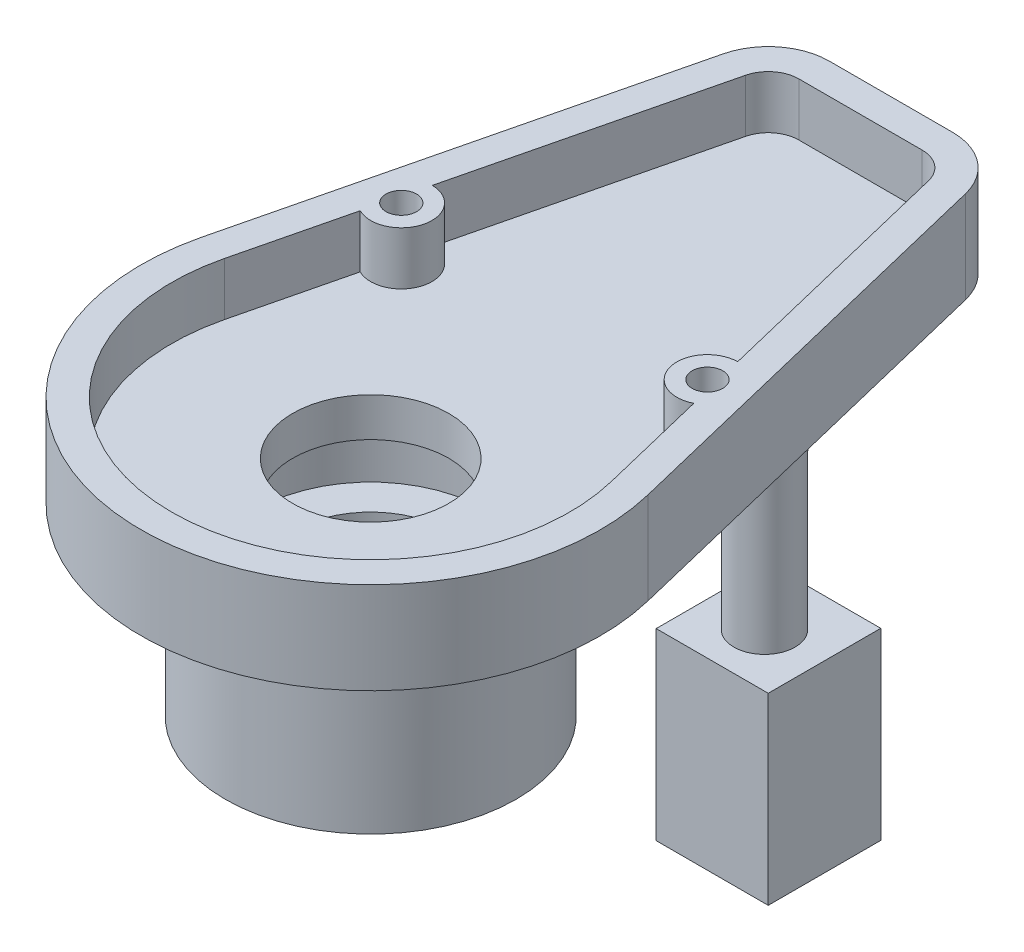
SolidWorks part; units mm, degrees
other "Markup2"
sketch "Sketch12"
other "Markup3"
sketch "Sketch13"
ref_plane "Front Plane" through (0, 0, 0) normal (0, 0, 1) x (1, 0, 0)
ref_plane "Top Plane" through (0, 0, 0) normal (0, 1, 0) x (1, 0, 0)
ref_plane "Right Plane" through (0, 0, 0) normal (1, 0, 0) x (0, 0, -1)
sketch "Sketch1" plane through (0, 0, 0) normal (0, 1, 0) x (1, 0, 0)
  line L0 (0, 0) -> (0, 0.16) construction
  line L1 (0.0201, 0.16) -> (-0.0201, 0.16)
  line L2 (-0.0299, 0.1524) -> (-0.0499, 0.07)
  line L3 (0.0299, 0.1524) -> (0.0499, 0.07)
  line L4 (-0.0396, 0.1547) -> (-0.0729, 0.0177)
  line L5 (0.0396, 0.1547) -> (0.0729, 0.0177)
  line L6 (0.0201, 0.17) -> (-0.0201, 0.17)
  line L7 (0, 0) -> (0, 0.06) construction
  line L8 (0.05, 0.06) -> (-0.05, 0.06) construction
  line L9 (-0.0545, 0.0511) -> (-0.0632, 0.0154)
  line L10 (0.0545, 0.0511) -> (0.0632, 0.0154)
  line L11 (-0.0299, 0.1524) -> (-0.0632, 0.0154) construction
  line L13 (0.0299, 0.1524) -> (0.0632, 0.0154) construction
  arc A1 (-0.0632, 0.0154) -> (0.0632, 0.0154) centre (0, 0) ccw
  arc A2 (0.0201, 0.16) -> (0.0299, 0.1524) centre (0.0201, 0.15) cw
  arc A3 (-0.0201, 0.16) -> (-0.0299, 0.1524) centre (-0.0201, 0.15) ccw
  arc A4 (-0.0729, 0.0177) -> (0.0729, 0.0177) centre (0, 0) ccw
  arc A5 (0.0201, 0.17) -> (0.0396, 0.1547) centre (0.0201, 0.15) cw
  arc A6 (-0.0201, 0.17) -> (-0.0396, 0.1547) centre (-0.0201, 0.15) ccw
  circle A7 centre (-0.05, 0.06) radius 0.005
  circle A8 centre (0.05, 0.06) radius 0.005
  arc A10 (-0.0545, 0.0511) -> (-0.0499, 0.07) centre (-0.05, 0.06) ccw
  arc A11 (0.0499, 0.07) -> (0.0545, 0.0511) centre (0.05, 0.06) ccw
  circle A12 centre (0.05, 0.06) radius 0.01 construction
  circle A13 centre (-0.05, 0.06) radius 0.01 construction
  point P8 (0, 0.16)
  point P13 (0, 0.06)
  point P17 (0.028, 0.16)
  point P20 (-0.028, 0.16)
  point P31 (0.06, 0.06)
  point P37 (-0.04, 0.06)
  dimension "D1" = 0.01
  dimension "D2" = 0.13
  dimension "D3" = 0.16
  dimension "D5" = 0.01
  dimension "D6" = 0.06
  dimension "D8" = 0.01
  dimension "D9" = 0.01
  dimension "D10" = 0.005
  dimension "D4" = 0.056
  dimension "D7" = 0.1
extrude "Boss-Extrude1" add sketch "Sketch1" along normal blind 0.03
sketch "Sketch6" plane through (0, 0, 0) normal (0, -1, 0) x (1, 0, 0)
  line L3 (-0.0201, -0.17) -> (0.0201, -0.17)
  line L4 (0.0396, -0.1547) -> (0.0729, -0.0177)
  line L5 (-0.0729, -0.0177) -> (-0.0396, -0.1547)
  line L6 (-0.0201, -0.17) -> (0.0201, -0.17)
  line L7 (0.0396, -0.1547) -> (0.0729, -0.0177)
  line L8 (-0.0729, -0.0177) -> (-0.0396, -0.1547)
  circle A0 centre (0, 0) radius 0.0255
  arc A1 (0.0632, -0.0154) -> (-0.0632, -0.0154) centre (0, 0) ccw construction
  arc A3 (-0.0396, -0.1547) -> (-0.0201, -0.17) centre (-0.0201, -0.15) ccw
  arc A4 (0.0201, -0.17) -> (0.0396, -0.1547) centre (0.0201, -0.15) ccw
  arc A5 (0.0729, -0.0177) -> (-0.0729, -0.0177) centre (0, 0) ccw
  arc A6 (-0.0396, -0.1547) -> (-0.0201, -0.17) centre (-0.0201, -0.15) ccw
  arc A7 (0.0201, -0.17) -> (0.0396, -0.1547) centre (0.0201, -0.15) ccw
  arc A8 (0.0729, -0.0177) -> (-0.0729, -0.0177) centre (0, 0) ccw
  dimension "D2" = 0.051
  dimension "D1" = 0
extrude "Boss-Extrude5" add sketch "Sketch6" against normal blind 0.0127
sketch "Sketch7" plane through (0, 0, 0) normal (0, -1, 0) x (1, 0, 0)
  circle A0 centre (0, 0) radius 0.0375
  circle A2 centre (0, 0) radius 0.0475
  dimension "D1" = 0.01
extrude "Boss-Extrude6" add sketch "Sketch7" along normal blind 0.06
ref_plane "cuck-ring-plane" through (0, -0.0205, 0) normal (0, -1, 0) x (-1, 0, 0)
sketch "Sketch8" plane through (0, -0.0205, 0) normal (0, -1, 0) x (-1, 0, 0)
  circle A0 centre (0, 0) radius 0.0375 construction
  circle A1 centre (0, 0) radius 0.0255 construction
  circle A2 centre (0, 0) radius 0.0375
  circle A3 centre (0, 0) radius 0.0255
extrude "Boss-Extrude7" add sketch "Sketch8" along normal blind 0.0253
sketch "Sketch9" plane through (0, 0, 0) normal (0, -1, 0) x (1, 0, 0)
  circle A0 centre (0, -0.1286) radius 0.01
  dimension "D1" = 0.02
extrude "Boss-Extrude8" add sketch "Sketch9" along normal blind 0.1
sketch "Sketch10" plane through (0, -0.1, 0) normal (0, -1, 0) x (1, 0, 0)
  line L1 (-0.01, -0.1186) -> (0.01, -0.1186) construction
  line L2 (-0.01, -0.1186) -> (-0.01, -0.1386) construction
  line L3 (-0.01, -0.1386) -> (0.01, -0.1386) construction
  line L4 (0.01, -0.1186) -> (0.01, -0.1386) construction
  line L5 (-0.0179, -0.1112) -> (0.0187, -0.1112)
  line L6 (-0.0179, -0.1112) -> (-0.0179, -0.148)
  line L7 (-0.0179, -0.148) -> (0.0187, -0.148)
  line L8 (0.0187, -0.1112) -> (0.0187, -0.148)
  circle A0 centre (0, -0.1286) radius 0.01 construction
  dimension "D1" = 0.0114
  dimension "D2" = 0.0079
  dimension "D3" = 0.0093
  dimension "D4" = 0.0109
extrude "Boss-Extrude9" add sketch "Sketch10" along normal blind 0.06
